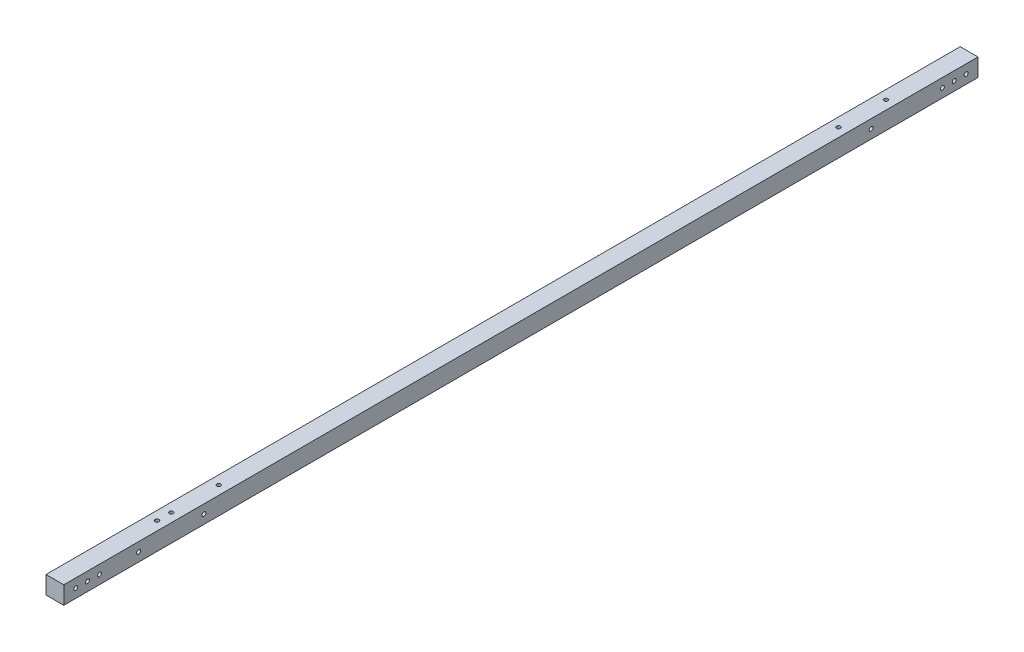
SolidWorks part; units mm, degrees
ref_plane "前视基准面" through (0, 0, 0) normal (0, 0, 1) x (1, 0, 0)
ref_plane "上视基准面" through (0, 0, 0) normal (0, 1, 0) x (1, 0, 0)
ref_plane "右视基准面" through (0, 0, 0) normal (1, 0, 0) x (0, 0, -1)
sketch "草图1" plane through (0, 0, 0) normal (0, 0, 1) x (1, 0, 0)
  line L1 (-7.5, -7.5) -> (7.5, -7.5)
  line L2 (-7.5, -7.5) -> (-7.5, 7.5)
  line L3 (-7.5, 7.5) -> (7.5, 7.5)
  line L4 (7.5, -7.5) -> (7.5, 7.5)
  line L5 (-7.5, -7.5) -> (7.5, 7.5) construction
  line L6 (-7.5, 7.5) -> (7.5, -7.5) construction
  point P0 (0, 0)
  dimension "D1" = 15
  dimension "D2" = 15
extrude "凸台-拉伸1" add sketch "草图1" along normal blind 657
sketch "草图2" plane through (0, -7.5, 0) normal (0, -1, 0) x (1, 0, 0)
  line L0 (0, 672.217) -> (0, -153.3062) construction
  line L1 (-7.5, 657) -> (7.5, 657) construction
  line L2 (-7.5, 0) -> (7.5, 0) construction
  circle A1 centre (0, 624) radius 1.65
  circle A2 centre (0, 612) radius 1.65
  circle A3 centre (0, 572) radius 1.65
  circle A4 centre (0, 10) radius 1.65
  circle A5 centre (0, 50) radius 1.65
  dimension "D4" = 3.3
  dimension "D5" = 45
  dimension "D6" = 85
  dimension "D7" = 3.3
  dimension "D8" = 3.3
  dimension "D10" = 3.3
  dimension "D12" = 3.3
  dimension "D3" = 33
  dimension "D9" = 10
  dimension "D11" = 50
extrude "切除-拉伸1" cut sketch "草图2" against normal blind 1000
sketch "草图4" plane through (7.5, 0, 0) normal (1, 0, 0) x (0, 0, -1)
  line L0 (-657, 0) -> (0, 0) construction
  line L1 (-657, -7.5) -> (-657, 7.5) construction
  line L2 (0, -7.5) -> (0, 7.5) construction
  circle A0 centre (-647, 0) radius 1.65
  circle A2 centre (-592, 0) radius 1.65
  circle A3 centre (-30, 0) radius 1.65
  dimension "D2" = 3.3
  dimension "D5" = 3.3
  dimension "D6" = 65
  dimension "D7" = 30
  dimension "D8" = 3.3
  dimension "D1" = 10
extrude "切除-拉伸2" cut sketch "草图4" against normal blind 20
sketch "草图5" plane through (0, 0, 0) normal (0, 0, -1) x (-1, 0, 0)
  line L1 (-7.5, -7.5) -> (7.5, -7.5)
  line L2 (-7.5, -7.5) -> (-7.5, 7.5)
  line L3 (-7.5, 7.5) -> (7.5, 7.5)
  line L4 (7.5, -7.5) -> (7.5, 7.5)
  line L5 (-7.5, -7.5) -> (7.5, 7.5) construction
  line L6 (-7.5, 7.5) -> (7.5, -7.5) construction
  point P0 (0, 0)
extrude "凸台-拉伸2" add sketch "草图5" along normal blind 20
sketch "草图6" plane through (0, 0, 657) normal (0, 0, 1) x (1, 0, 0)
  line L1 (-7.5, -7.5) -> (7.5, -7.5)
  line L2 (-7.5, -7.5) -> (-7.5, 7.5)
  line L3 (-7.5, 7.5) -> (7.5, 7.5)
  line L4 (7.5, -7.5) -> (7.5, 7.5)
  line L5 (-7.5, -7.5) -> (7.5, 7.5) construction
  line L6 (-7.5, 7.5) -> (7.5, -7.5) construction
  point P0 (0, 0)
extrude "凸台-拉伸3" add sketch "草图6" along normal blind 23
sketch "草图7" plane through (0, 0, 680) normal (0, 0, 1) x (1, 0, 0)
  line L4 (7.5, -7.5) -> (7.5, 7.5)
  line L5 (7.5, 7.5) -> (-7.5, 7.5)
  line L6 (-7.5, 7.5) -> (-7.5, -7.5)
  line L7 (-7.5, -7.5) -> (7.5, -7.5)
  line L8 (7.5, -7.5) -> (7.5, 7.5)
  line L9 (7.5, 7.5) -> (-7.5, 7.5)
  line L10 (-7.5, 7.5) -> (-7.5, -7.5)
  line L11 (-7.5, -7.5) -> (7.5, -7.5)
  dimension "D1" = 0
extrude "凸台-拉伸4" add sketch "草图7" along normal blind 30
sketch "草图8" plane through (0, 0, -20) normal (0, 0, -1) x (-1, 0, 0)
  line L4 (7.5, -7.5) -> (7.5, 7.5)
  line L5 (7.5, 7.5) -> (-7.5, 7.5)
  line L6 (-7.5, 7.5) -> (-7.5, -7.5)
  line L7 (-7.5, -7.5) -> (7.5, -7.5)
  line L8 (7.5, -7.5) -> (7.5, 7.5)
  line L9 (7.5, 7.5) -> (-7.5, 7.5)
  line L10 (-7.5, 7.5) -> (-7.5, -7.5)
  line L11 (-7.5, -7.5) -> (7.5, -7.5)
  dimension "D1" = 0
extrude "凸台-拉伸5" add sketch "草图8" along normal blind 30
sketch "草图9" plane through (0, 0, -50) normal (0, 0, -1) x (-1, 0, 0)
  line L4 (-7.5, -7.5) -> (7.5, -7.5)
  line L5 (7.5, -7.5) -> (7.5, 7.5)
  line L6 (7.5, 7.5) -> (-7.5, 7.5)
  line L7 (-7.5, 7.5) -> (-7.5, -7.5)
  line L8 (-7.5, -7.5) -> (7.5, -7.5)
  line L9 (7.5, -7.5) -> (7.5, 7.5)
  line L10 (7.5, 7.5) -> (-7.5, 7.5)
  line L11 (-7.5, 7.5) -> (-7.5, -7.5)
  dimension "D1" = 0
extrude "凸台-拉伸6" add sketch "草图9" along normal blind 10
sketch "草图10" plane through (-7.5, 0, 0) normal (-1, 0, 0) x (0, 0, 1)
  line L0 (-67.1801, 0) -> (732.8528, 0) construction
  line L1 (-60, -7.5) -> (-60, 7.5) construction
  line L2 (710, 7.5) -> (710, -7.5) construction
  circle A0 centre (-50, 0) radius 1.65
  circle A1 centre (-40, 0) radius 1.65
  circle A2 centre (-30, 0) radius 1.65
  circle A3 centre (680, 0) radius 1.65
  circle A4 centre (690, 0) radius 1.65
  circle A5 centre (700, 0) radius 1.65
  dimension "D1" = 3.3
  dimension "D2" = 3.3
  dimension "D3" = 3.3
  dimension "D4" = 10
  dimension "D5" = 10
  dimension "D6" = 10
  dimension "D7" = 3.3
  dimension "D8" = 3.3
  dimension "D9" = 3.3
  dimension "D10" = 10
  dimension "D11" = 10
  dimension "D12" = 10
extrude "切除-拉伸3" cut sketch "草图10" against normal blind 20
